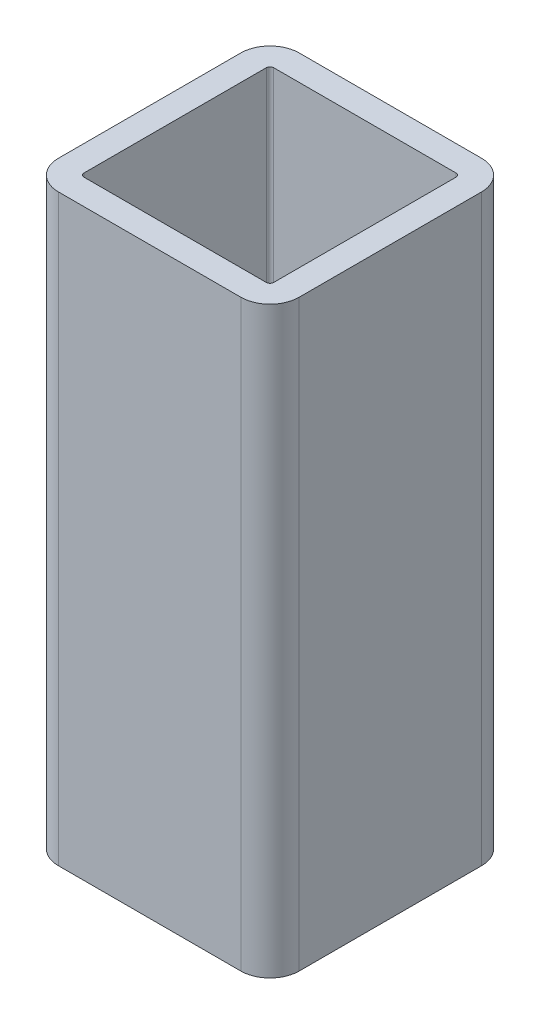
SolidWorks part; units mm, degrees
ref_plane "Front Plane" through (0, 0, 0) normal (0, 0, 1) x (1, 0, 0)
ref_plane "Top Plane" through (0, 0, 0) normal (0, 1, 0) x (1, 0, 0)
ref_plane "Right Plane" through (0, 0, 0) normal (1, 0, 0) x (0, 0, -1)
sketch "Sketch1" plane through (0, 0, 0) normal (0, 1, 0) x (1, 0, 0)
  line L0 (24.1947, 16.9333) -> (24.1947, -22.7542)
  line L1 (-16.2866, 23.2833) -> (23.4009, 23.2833)
  line L2 (-22.6366, 16.9333) -> (-22.6366, -22.7542)
  line L3 (-16.2866, -29.1042) -> (23.4009, -29.1042)
  line L4 (29.7509, 16.9333) -> (29.7509, -22.7542)
  line L5 (-16.2866, -23.5479) -> (23.4009, -23.5479)
  line L6 (-17.0803, 16.9333) -> (-17.0803, -22.7542)
  line L7 (-16.2866, 17.7271) -> (23.4009, 17.7271)
  arc A0 (29.7509, -22.7542) -> (23.4009, -29.1042) centre (23.4009, -22.7542) cw
  arc A1 (-22.6366, -22.7542) -> (-16.2866, -29.1042) centre (-16.2866, -22.7542) ccw
  arc A2 (-16.2866, 23.2833) -> (-22.6366, 16.9333) centre (-16.2866, 16.9333) ccw
  arc A3 (23.4009, 23.2833) -> (29.7509, 16.9333) centre (23.4009, 16.9333) cw
  arc A4 (24.1947, -22.7542) -> (23.4009, -23.5479) centre (23.4009, -22.7542) cw
  arc A5 (-17.0803, -22.7542) -> (-16.2866, -23.5479) centre (-16.2866, -22.7542) ccw
  arc A6 (-16.2866, 17.7271) -> (-17.0803, 16.9333) centre (-16.2866, 16.9333) ccw
  arc A7 (23.4009, 17.7271) -> (24.1947, 16.9333) centre (23.4009, 16.9333) cw
  point P8 (-22.6366, -29.1042)
  point P11 (-22.6366, 23.2833)
  point P14 (29.7509, 23.2833)
  dimension "D3" = 6.35
  dimension "D1" = 52.3875
  dimension "D2" = 52.3875
  dimension "D4" = 5.5562
extrude "Boss-Extrude1" add sketch "Sketch1" along normal blind 127
